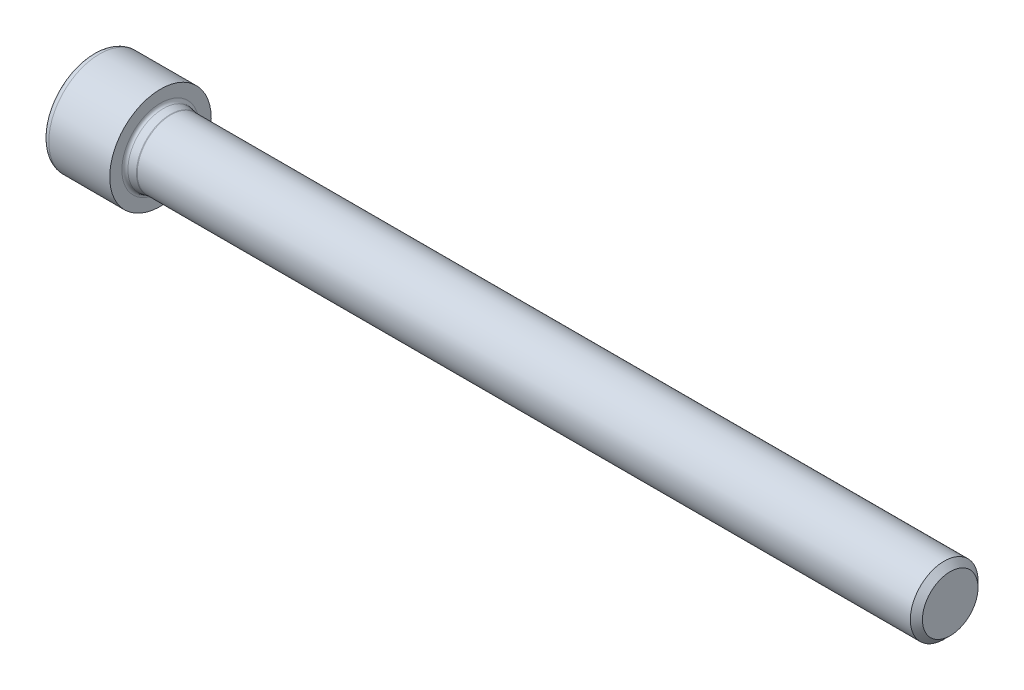
SolidWorks part; units mm, degrees
material "Material"
ref_plane "Front Plane" through (0, 0, 0) normal (0, 0, 1) x (1, 0, 0)
ref_plane "Top Plane" through (0, 0, 0) normal (0, 1, 0) x (1, 0, 0)
ref_plane "Right Plane" through (0, 0, 0) normal (1, 0, 0) x (0, 0, -1)
sketch "Sketch1" plane through (0, 0, 0) normal (0, 0, 1) x (1, 0, 0)
  line L0 (-12, 9) -> (-12, 0)
  line L1 (-12, 0) -> (0, 0)
  line L2 (0, 0) -> (0, 9)
  line L3 (0, 9) -> (-12, 9)
  line L4 (-12, 0) -> (0, 0) construction
  dimension "D1" = 12
  dimension "D2" = 9
revolve "Revolve1" add sketch "Sketch1" angle 360 about L4
ref_plane "Plane1" through (-10.7273, 0, 0) normal (-1, 0, 0) x (0, 0, 1)
sketch "Sketch2" plane through (-10.7273, 0, 0) normal (-1, 0, 0) x (0, 0, 1)
  line L0 (-2.5417, 4.3061) -> (-2.494, 4.3336)
  line L1 (-2.494, 4.3336) -> (-2.4583, 4.3542)
  line L2 (-2.4583, 4.3542) -> (0, 5.7735)
  line L3 (0, 5.7735) -> (2.4583, 4.3542)
  line L4 (2.4583, 4.3542) -> (2.506, 4.3267)
  line L5 (2.506, 4.3267) -> (2.5417, 4.3061)
  line L6 (2.5417, 4.3061) -> (5, 2.8868)
  line L7 (5, 2.8868) -> (5, 0.0481)
  line L8 (5, 0.0481) -> (5, -0.0012)
  line L9 (5, -0.0012) -> (5, -0.0481)
  line L10 (5, -0.0481) -> (5, -2.8868)
  line L11 (5, -2.8868) -> (2.5417, -4.3061)
  line L12 (2.5417, -4.3061) -> (2.494, -4.3336)
  line L13 (2.494, -4.3336) -> (2.4583, -4.3542)
  line L14 (2.4583, -4.3542) -> (0, -5.7735)
  line L15 (0, -5.7735) -> (-2.4583, -4.3542)
  line L16 (-2.4583, -4.3542) -> (-2.506, -4.3267)
  line L17 (-2.506, -4.3267) -> (-2.5417, -4.3061)
  line L18 (-2.5417, -4.3061) -> (-5, -2.8868)
  line L19 (-5, -2.8868) -> (-5, -0.0481)
  line L20 (-5, -0.0481) -> (-5, -0.0012)
  line L21 (-5, -0.0012) -> (-5, 0.0481)
  line L22 (-5, 0.0481) -> (-5, 2.8868)
  line L23 (-5, 2.8868) -> (-2.5417, 4.3061)
  dimension "D1" = 10
  dimension "D2" = 2.4583
  dimension "D3" = 0.0357
  dimension "D4" = 0.012
  dimension "D5" = 0.0357
  dimension "D6" = 2.4583
  dimension "D7" = 2.4583
  dimension "D8" = 0.0357
  dimension "D9" = 0.012
  dimension "D10" = 0.0357
  dimension "D11" = 11.547
  dimension "D12" = 1.4193
  dimension "D13" = 0.0206
  dimension "D14" = 0.0069
  dimension "D15" = 0.0206
  dimension "D16" = 1.4193
  dimension "D17" = 2.8386
  dimension "D18" = 0.047
  dimension "D19" = 0.0493
  dimension "D20" = 2.8386
  dimension "D21" = 1.4193
  dimension "D22" = 0.0206
  dimension "D23" = 0.0069
  dimension "D24" = 0.0206
extrude "Cut-Extrude1" cut sketch "Sketch2" against normal blind 0.4242 from surface at 1.2727 starting at face at (-12, 0, -9)
sketch "Sketch3" plane through (-11.5758, 0, 0) normal (-1, 0, 0) x (0, 0, 1)
  line L0 (0, 5.7735) -> (-5, 2.8868)
  line L1 (-5, 2.8868) -> (-5, -2.8868)
  line L2 (-5, -2.8868) -> (0, -5.7735)
  line L3 (0, -5.7735) -> (5, -2.8868)
  line L4 (5, -2.8868) -> (5, 2.8868)
  line L5 (5, 2.8868) -> (0, 5.7735)
  dimension "D1" = 5
  dimension "D2" = 5
  dimension "D3" = 11.547
  dimension "D4" = 2.8868
  dimension "D5" = 5.7735
extrude "Cut-Extrude2" cut sketch "Sketch3" against normal blind 5.5758
sketch "Sketch4" plane through (0, 0, 0) normal (1, 0, 0) x (0, 0, -1)
  circle A0 centre (0, 0) radius 6.3566
  dimension "D1" = 12.7132
extrude "Boss-Extrude1" add sketch "Sketch4" along normal blind 1.8115 draft 11.136
sketch "Sketch5" plane through (1.8115, 0, 0) normal (1, 0, 0) x (0, 0, -1)
  circle A0 centre (0, 0) radius 6
  dimension "D1" = 12
extrude "Boss-Extrude2" add sketch "Sketch5" along normal blind 138.1885
sketch "Sketch6" plane through (0, 0, 0) normal (0, 0, 1) x (1, 0, 0)
  line L0 (-6, 5) -> (-6, 0)
  line L1 (-6, 0) -> (-3.1132, 0)
  line L2 (-3.1132, 0) -> (-6, 5)
  line L3 (-6, 0) -> (-3.1132, 0) construction
  dimension "D1" = 2.8868
  dimension "D2" = 5
revolve "Cut-Revolve1" cut sketch "Sketch6" angle 360 about L3
chamfer "Chamfer1" distance 1.0735 angle 45 1 edges at (140, 0, -6)
fillet "Fillet1" radius 0.6 2 edges at (1.8115, 0, -6) (0, 0, -6.3566)
fillet "Fillet2" radius 1.2 1 edges at (-12, 0, -9)
